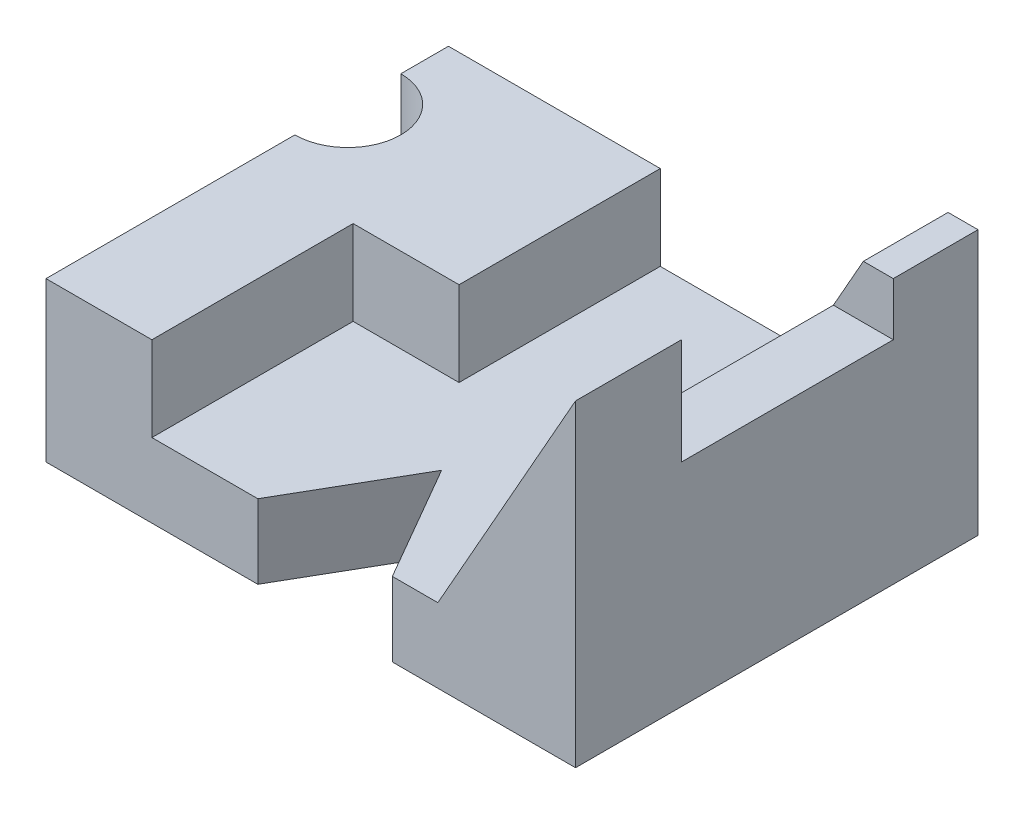
SolidWorks part; units mm, degrees
ref_plane "Спереди" through (0, 0, 0) normal (0, 0, 1) x (1, 0, 0)
ref_plane "Сверху" through (0, 0, 0) normal (0, 1, 0) x (1, 0, 0)
ref_plane "Справа" through (0, 0, 0) normal (1, 0, 0) x (0, 0, -1)
sketch "Эскиз1" plane through (0, 0, 0) normal (0, 0, 1) x (1, 0, 0)
  line L0 (-25, 0) -> (-5, 0)
  line L1 (-25, -15) -> (25, -15)
  line L2 (-25, -15) -> (-25, 15)
  line L3 (-25, 15) -> (25, 15)
  line L4 (25, -15) -> (25, 15)
  line L5 (-25, -15) -> (25, 15) construction
  line L6 (-25, 15) -> (25, -15) construction
  line L7 (-5, 0) -> (-5, -8)
  line L8 (-5, -8) -> (12, -8)
  line L9 (12, -8) -> (25, 15)
  point P0 (0, 0)
  dimension "D1" = 50
  dimension "D2" = 30
  dimension "D3" = 20
  dimension "D4" = 17
  dimension "D5" = 7
extrude "Бобышка-Вытянуть1" add sketch "Эскиз1" along normal blind 38 contours L9 L8 L7 L0 L2 L1 L4
sketch "Эскиз2" plane through (0, 0, 0) normal (0, 1, 0) x (1, 0, 0)
  line L0 (-5, -38) -> (-5, 0) construction
  line L1 (-5, -19) -> (-15, -19)
  line L2 (-5, -19) -> (-5, -38)
  line L3 (-5, -38) -> (-15, -38)
  line L4 (-15, -19) -> (-15, -38)
  line L5 (-25, -38) -> (-5, -38) construction
  line L6 (-25, -38) -> (-25, 0) construction
  line L8 (-5, -19) -> (-5, 0) construction
  line L9 (-5, -9.5) -> (-25, -9.5) construction
  circle A0 centre (-25, -9.5) radius 5
  dimension "D1" = 10
extrude "Вырез-Вытянуть1" cut sketch "Эскиз2" against normal up to surface (8 mm away) up to face at (3.5, -8, 19)
sketch "Эскиз3" plane through (0, -8, 0) normal (0, 1, 0) x (1, 0, 0)
  line L0 (-25, -14.5) -> (-25, -4.5) construction
  line L1 (-27, -11.5) -> (-23, -11.5)
  line L2 (-27, -11.5) -> (-27, -7.5)
  line L3 (-27, -7.5) -> (-23, -7.5)
  line L4 (-23, -11.5) -> (-23, -7.5)
  line L5 (-27, -11.5) -> (-23, -7.5) construction
  line L6 (-27, -7.5) -> (-23, -11.5) construction
  line L7 (-5, -19) -> (-5, 0) construction
  line L9 (-15, -38) -> (12, -38) construction
  line L10 (1.3509, -27) -> (7.7017, -38)
  line L11 (7.7017, -38) -> (-5, -38)
  line L12 (1.3509, -27) -> (-5, -38)
  point P0 (-25, -9.5)
  dimension "D1" = 4
  dimension "D3" = 11
extrude "Вырез-Вытянуть2" cut sketch "Эскиз3" against normal through all
sketch "Эскиз4" plane through (25, 0, 0) normal (1, 0, 0) x (0, 0, -1)
  line L0 (-38, 15) -> (0, 15) construction
  line L1 (-8, 15) -> (-28, 15)
  line L2 (-8, 10) -> (-8, 5)
  line L3 (-8, 5) -> (-28, 5)
  line L4 (-28, 15) -> (-28, 5)
  line L5 (0, -15) -> (0, 15) construction
  line L7 (-8, 15) -> (0, 15)
  line L9 (-8, 10) -> (0, 10)
  line L10 (0, 15) -> (0, 10)
  dimension "D1" = 10
  dimension "D2" = 8
  dimension "D3" = 20
  dimension "D4" = 5
extrude "Вырез-Вытянуть3" cut sketch "Эскиз4" against normal through all
